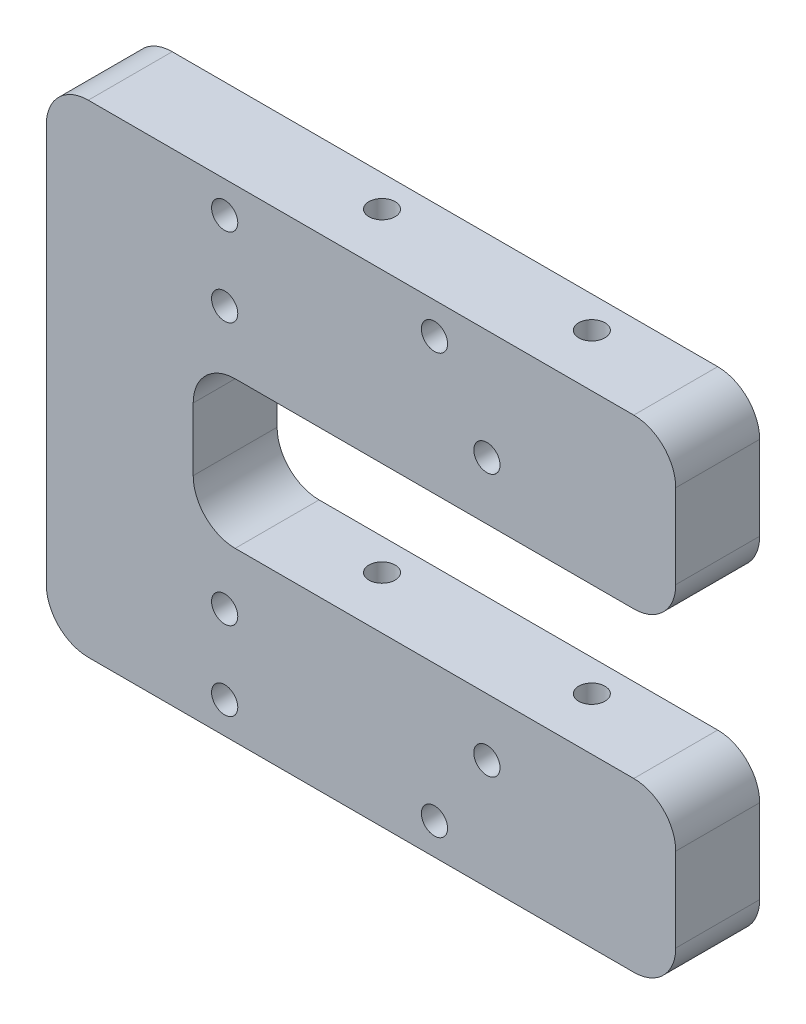
SolidWorks part; units mm, degrees
material "6061 合金"
ref_plane "前视基准面" through (0, 0, 0) normal (0, 0, 1) x (1, 0, 0)
ref_plane "上视基准面" through (0, 0, 0) normal (0, 1, 0) x (1, 0, 0)
ref_plane "右视基准面" through (0, 0, 0) normal (1, 0, 0) x (0, 0, -1)
other "Configuration Table"
sketch "草图1" plane through (0, 0, 0) normal (0, 0, 1) x (1, 0, 0)
  line L0 (0, 23) -> (95.8228, 23) construction
  line L1 (0, 0) -> (60, 0)
  line L2 (0, 0) -> (0, 46)
  line L3 (0, 46) -> (60, 46)
  line L4 (60, 0) -> (60, 16)
  line L5 (14, 16) -> (60, 16)
  line L7 (14, 16) -> (14, 30)
  line L8 (14, 30) -> (60, 30)
  line L10 (60, 30) -> (60, 46)
  line L11 (14, 16) -> (60, 16)
  circle A0 centre (17, 35.5) radius 1.25
  circle A1 centre (42, 35.5) radius 1.25
  circle A2 centre (42, 10.5) radius 1.25
  circle A3 centre (17, 10.5) radius 1.25
  dimension "D6" = 25
  dimension "3.2" = 2.5
  dimension "D7" = 25
  dimension "D8" = 17
  dimension "D1" = 60
  dimension "D2" = 46
  dimension "D3" = 46
  dimension "D4" = 7
  dimension "D5" = 2
extrude "凸台-拉伸1" add sketch "草图1" along normal blind 8 contours L2 L0 L7 L8 L10 L3 A0 A1 | L0 L2 L1 L4 L5 L7 A2 A3
fillet "圆角1" radius 4 8 edges at (0, 46, 4) (60, 46, 4) (60, 30, 4) (14, 30, 4) (14, 16, 4) (60, 16, 4) (0, 0, 4) (60, 0, 4)
sketch "草图2" plane through (0, 0, 8) normal (0, 0, 1) x (1, 0, 0)
  line L0 (0, 4) -> (0, 42) construction
  line L1 (0, 23) -> (82.9703, 23) construction
  circle A0 centre (17, 3) radius 1.25
  circle A2 centre (37, 3) radius 1.25
  circle A3 centre (37, 43) radius 1.25
  circle A4 centre (17, 43) radius 1.25
  dimension "D1" = 2.5
  dimension "D2" = 17
  dimension "D4" = 40
  dimension "D5" = 20
  dimension "D3" = 2
extrude "切除-拉伸1" cut sketch "草图2" against normal blind 10
sketch "草图3" plane through (0, 46, 0) normal (0, 1, 0) x (1, 0, 0)
  line L0 (0, -8) -> (0, 0) construction
  line L1 (4, 0) -> (56, 0) construction
  circle A0 centre (27, -3) radius 1.25
  circle A1 centre (47, -3) radius 1.25
  point P8 (30, 0)
  dimension "D1" = 2.5
  dimension "D4" = 20
  dimension "D5" = 3
  dimension "D2" = 27
  dimension "D3" = 2
extrude "切除-拉伸2" cut sketch "草图3" against normal blind 67
